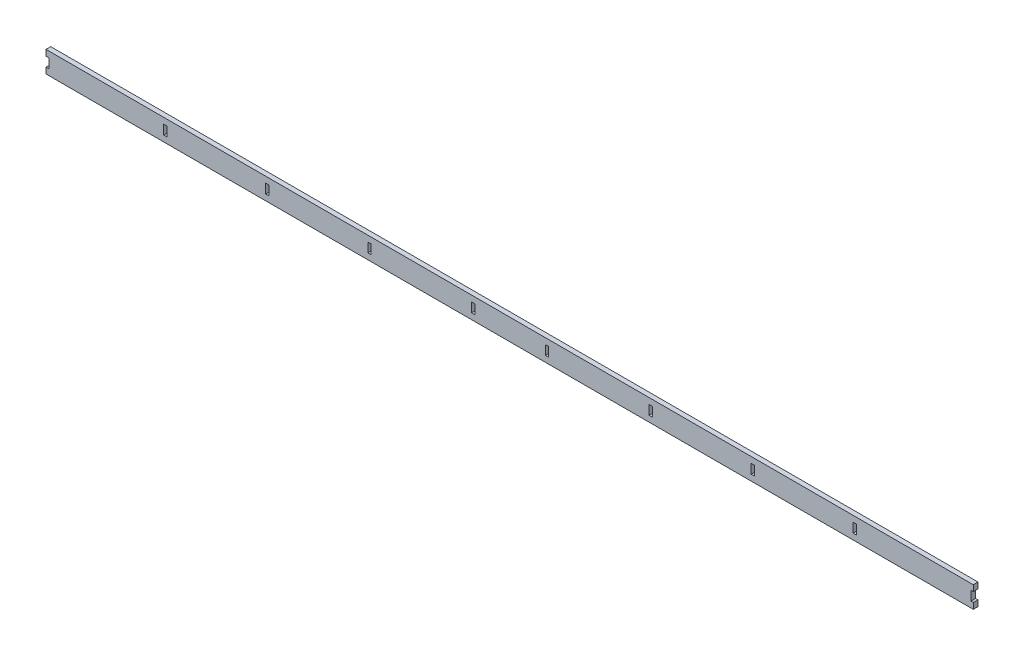
SolidWorks part; units mm, degrees
ref_plane "前视基准面" through (0, 0, 0) normal (0, 0, 1) x (1, 0, 0)
ref_plane "上视基准面" through (0, 0, 0) normal (0, 1, 0) x (1, 0, 0)
ref_plane "右视基准面" through (0, 0, 0) normal (1, 0, 0) x (0, 0, -1)
sketch "Model" plane through (0, 0, 0) normal (0, 0, 1) x (1, 0, 0)
  line L0 (594.4799, 20.9668) -> (3.6836, 20.9668)
  line L1 (3.6836, 20.9668) -> (3.6836, 17.1668)
  line L2 (3.6836, 11.1668) -> (3.6836, 7.3668)
  line L3 (3.6836, 7.3668) -> (594.4799, 7.3668)
  line L4 (594.4799, 20.9668) -> (594.4799, 17.1668)
  line L5 (594.4799, 11.1668) -> (594.4799, 7.3668)
  line L6 (594.4799, 17.1668) -> (592.9799, 17.1668)
  line L7 (592.9799, 17.1668) -> (592.9799, 11.1668)
  line L8 (592.9799, 11.1668) -> (594.4799, 11.1668)
  line L9 (3.6836, 17.1668) -> (5.6836, 17.1668)
  line L10 (5.6836, 17.1668) -> (5.6836, 11.1668)
  line L11 (5.6836, 11.1668) -> (3.6836, 11.1668)
  line L12 (78.6836, 14.1668) -> (78.6836, 17.1668)
  line L13 (78.6836, 11.1668) -> (78.6836, 14.1668)
  line L14 (143.6836, 14.1668) -> (143.6836, 17.1668)
  line L15 (143.6836, 11.1668) -> (143.6836, 14.1668)
  line L16 (208.6836, 14.1668) -> (208.6836, 17.1668)
  line L17 (208.6836, 11.1668) -> (208.6836, 14.1668)
  line L18 (274.8835, 14.1668) -> (274.8835, 17.1668)
  line L19 (274.8835, 11.1668) -> (274.8835, 14.1668)
  line L20 (321.8836, 14.1668) -> (321.8836, 17.1668)
  line L21 (321.8836, 11.1668) -> (321.8836, 14.1668)
  line L22 (387.9799, 14.1668) -> (387.9799, 17.1668)
  line L23 (387.9799, 11.1668) -> (387.9799, 14.1668)
  line L24 (452.9799, 14.1668) -> (452.9799, 17.1668)
  line L25 (452.9799, 11.1668) -> (452.9799, 14.1668)
  line L26 (517.9799, 14.1668) -> (517.9799, 17.1668)
  line L27 (517.9799, 11.1668) -> (517.9799, 14.1668)
  line L28 (78.6836, 17.1668) -> (80.6836, 17.1668)
  line L29 (80.6836, 17.1668) -> (80.6836, 11.1668)
  line L30 (80.6836, 11.1668) -> (78.6836, 11.1668)
  line L31 (143.6836, 17.1668) -> (145.6836, 17.1668)
  line L32 (145.6836, 17.1668) -> (145.6836, 11.1668)
  line L33 (145.6836, 11.1668) -> (143.6836, 11.1668)
  line L34 (208.6836, 17.1668) -> (210.6836, 17.1668)
  line L35 (210.6836, 17.1668) -> (210.6836, 11.1668)
  line L36 (210.6836, 11.1668) -> (208.6836, 11.1668)
  line L37 (274.8835, 17.1668) -> (276.8835, 17.1668)
  line L38 (276.8835, 17.1668) -> (276.8835, 11.1668)
  line L39 (276.8835, 11.1668) -> (274.8835, 11.1668)
  line L40 (321.8836, 17.1668) -> (323.8836, 17.1668)
  line L41 (323.8836, 17.1668) -> (323.8836, 11.1668)
  line L42 (323.8836, 11.1668) -> (321.8836, 11.1668)
  line L43 (387.9799, 17.1668) -> (389.9799, 17.1668)
  line L44 (389.9799, 17.1668) -> (389.9799, 11.1668)
  line L45 (389.9799, 11.1668) -> (387.9799, 11.1668)
  line L46 (452.9799, 17.1668) -> (454.9799, 17.1668)
  line L47 (454.9799, 17.1668) -> (454.9799, 11.1668)
  line L48 (454.9799, 11.1668) -> (452.9799, 11.1668)
  line L49 (517.9799, 17.1668) -> (519.9799, 17.1668)
  line L50 (519.9799, 17.1668) -> (519.9799, 11.1668)
  line L51 (519.9799, 11.1668) -> (517.9799, 11.1668)
extrude "凸台-拉伸1" add sketch "Model" along normal blind 3
